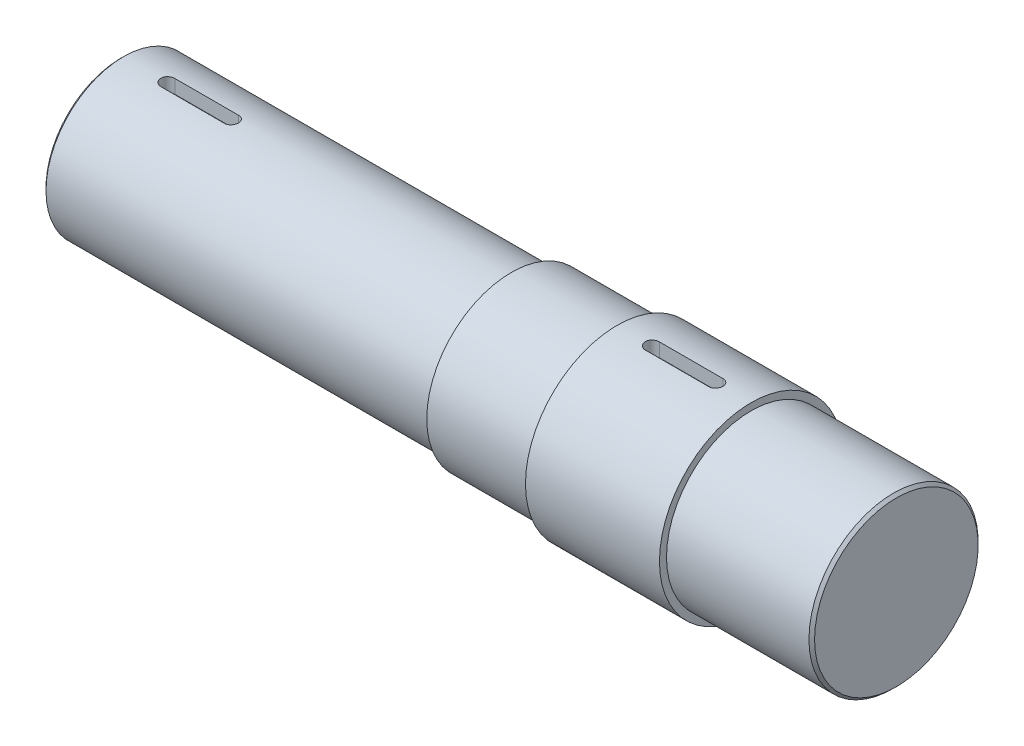
SolidWorks part; units mm, degrees
ref_plane "Alzado" through (0, 0, 0) normal (0, 0, 1) x (1, 0, 0)
ref_plane "Planta" through (0, 0, 0) normal (0, 1, 0) x (1, 0, 0)
ref_plane "Vista lateral" through (0, 0, 0) normal (1, 0, 0) x (0, 0, -1)
sketch "Croquis1" plane through (0, 0, 0) normal (0, 1, 0) x (1, 0, 0)
  line L11 (0, 0) -> (550, 0)
  line L12 (550, 0) -> (550, 60)
  line L13 (550, 60) -> (447, 60)
  line L14 (447, 60) -> (447, 65)
  line L15 (447, 65) -> (352, 65)
  line L16 (352, 65) -> (352, 60)
  line L17 (352, 60) -> (277, 60)
  line L18 (277, 60) -> (277, 55)
  line L19 (277, 55) -> (0, 55)
  line L20 (0, 55) -> (0, 0)
  dimension "D1" = 60
  dimension "D2" = 55
  dimension "D3" = 60
  dimension "D4" = 65
  dimension "D5" = 277
  dimension "D6" = 75
  dimension "D7" = 95
  dimension "D8" = 550
revolve "Revolución2" add sketch "Croquis1" angle 360 about L11
chamfer "Chaflán1" distance 2 angle 45 1 edges at (0, 0, 55)
chamfer "Chaflán2" distance 2 angle 45 1 edges at (550, 0, 60)
ref_plane "Plano1" through (0, 65, 0) normal (0, 1, 0) x (1, 0, 0)
sketch "Croquis2" plane through (0, 65, 0) normal (0, 1, 0) x (1, 0, 0)
  line L0 (377, -5) -> (422, -5)
  line L2 (377, 0) -> (422, 0)
  line L3 (377, 5) -> (422, 5)
  arc A0 (377, -5) -> (377, 5) centre (377, 0) cw
  arc A1 (422, -5) -> (422, 5) centre (422, 0) ccw
  dimension "D1" = 5
  dimension "D2" = 5
extrude "Cortar-Extruir1" cut sketch "Croquis2" against normal blind 10
ref_plane "Plano2" through (0, 55, 0) normal (0, 1, 0) x (1, 0, 0)
sketch "Croquis3" plane through (0, 55, 0) normal (0, 1, 0) x (1, 0, 0)
  line L0 (33.4902, -5) -> (78.4902, -5)
  line L1 (33.4902, 0) -> (78.4902, 0)
  line L2 (33.4902, 5) -> (78.4902, 5)
  arc A0 (33.4902, -5) -> (33.4902, 5) centre (33.4902, 0) cw
  arc A1 (78.4902, -5) -> (78.4902, 5) centre (78.4902, 0) ccw
  dimension "D1" = 5
  dimension "D2" = 5
extrude "Cortar-Extruir2" cut sketch "Croquis3" against normal blind 10 contours L0 A1 L2 A0
